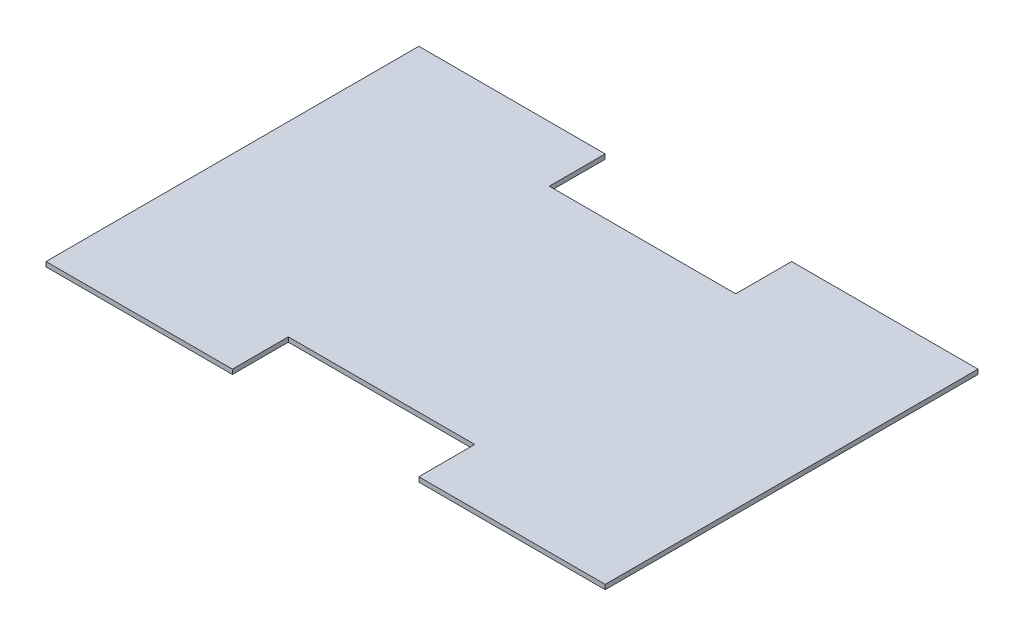
SolidWorks part; units mm, degrees
ref_plane "Front Plane" through (0, 0, 0) normal (0, 0, 1) x (1, 0, 0)
ref_plane "Top Plane" through (0, 0, 0) normal (0, 1, 0) x (1, 0, 0)
ref_plane "Right Plane" through (0, 0, 0) normal (1, 0, 0) x (0, 0, -1)
sketch "Sketch1" plane through (0, 0, 0) normal (0, 1, 0) x (1, 0, 0)
  line L1 (-300, -200) -> (300, -200)
  line L2 (-300, -200) -> (-300, 200)
  line L3 (-300, 200) -> (300, 200)
  line L4 (300, -200) -> (300, 200)
  line L5 (-300, -200) -> (300, 200) construction
  line L6 (-300, 200) -> (300, -200) construction
  point P0 (0, 0)
  dimension "D1" = 600
  dimension "D2" = 400
extrude "Boss-Extrude1" add sketch "Sketch1" along normal blind 5
sketch "Sketch2" plane through (0, 5, 0) normal (0, 1, 0) x (1, 0, 0)
  line L0 (300, 200) -> (-300, 200) construction
  line L1 (-100, 200) -> (100, 200)
  line L2 (-100, 200) -> (-100, 140)
  line L3 (-100, 140) -> (100, 140)
  line L4 (100, 200) -> (100, 140)
  line L5 (0, 0) -> (0, 200) construction
  line L6 (0, 0) -> (37.0021, 0)
  line L7 (-100, -140) -> (100, -140)
  line L8 (100, -200) -> (100, -140)
  line L9 (-100, -200) -> (100, -200)
  line L10 (-100, -200) -> (-100, -140)
  point P8 (0, 200)
  line M8 (300, 200) -> (-300, 200)
  line M10 (-300, -200) -> (300, -200)
  dimension "D1" = 200
  dimension "D2" = 60
extrude "Cut-Extrude1" cut sketch "Sketch2" against normal through all contours L3 L5 L1 L2 | L5 L3 L4 M8 | L10 L8 L7 M10
